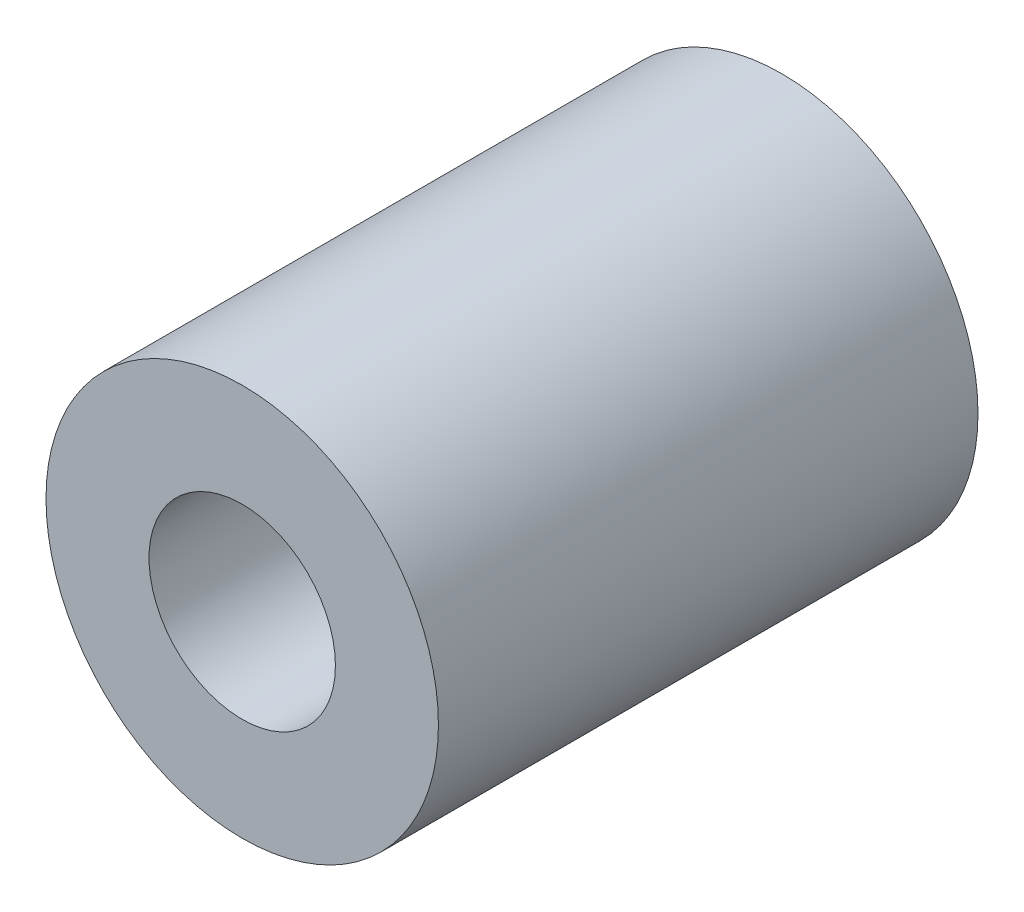
SolidWorks part; units mm, degrees
ref_plane "Front Plane" through (0, 0, 0) normal (0, 0, 1) x (1, 0, 0)
ref_plane "Top Plane" through (0, 0, 0) normal (0, 1, 0) x (1, 0, 0)
ref_plane "Right Plane" through (0, 0, 0) normal (1, 0, 0) x (0, 0, -1)
sketch "Sketch1" plane through (0, 0, 0) normal (0, 0, 1) x (1, 0, 0)
  line L0 (0, 0) -> (1.6, 0) construction
  line L1 (0, 0) -> (-1.6, 0) construction
  line L2 (-1.6, 0) -> (-1.6, 2.6)
  line L3 (-1.6, 2.6) -> (1.6, 2.6)
  line L4 (1.6, 2.6) -> (1.6, -2.6)
  line L5 (1.6, -2.6) -> (-1.6, -2.6)
  line L6 (-1.6, -2.6) -> (-1.6, 0)
  circle A0 centre (0, 0) radius 4
extrude "Boss-Extrude1" add sketch "Sketch1" along normal blind 7
sketch "Sketch2" plane through (0, 0, 7) normal (0, 0, 1) x (1, 0, 0)
  circle A0 centre (0, 0) radius 4
extrude "Boss-Extrude2" add sketch "Sketch2" along normal blind 4
sketch "Sketch3" plane through (0, 0, 11) normal (0, 0, 1) x (1, 0, 0)
  circle A0 centre (0, 0) radius 1.9
extrude "Cut-Extrude1" cut sketch "Sketch3" against normal blind 4
